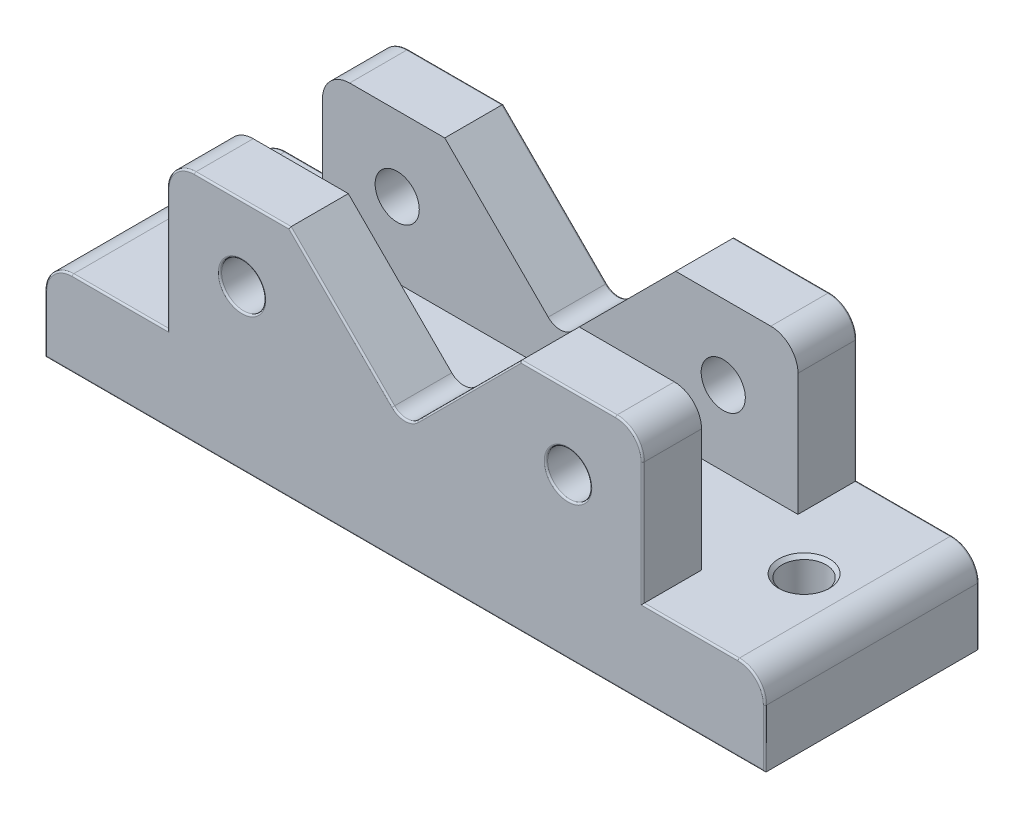
SolidWorks part; units mm, degrees
ref_plane "Płaszczyzna przednia" through (0, 0, 0) normal (0, 0, 1) x (1, 0, 0)
ref_plane "Płaszczyzna górna" through (0, 0, 0) normal (0, 1, 0) x (1, 0, 0)
ref_plane "Płaszczyzna prawa" through (0, 0, 0) normal (1, 0, 0) x (0, 0, -1)
sketch "Sketch1" plane through (0, 0, 0) normal (0, 0, 1) x (1, 0, 0)
  line L0 (0, 50) -> (0, 0) construction
  line L1 (0, 0) -> (106, 0) construction
  line L2 (0, 0) -> (0, 17)
  line L3 (8, 25) -> (36, 25)
  line L4 (36, 25) -> (36, 61)
  line L5 (44, 69) -> (72, 69)
  line L6 (72, 69) -> (102.4645, 38.5355)
  line L7 (106, 0) -> (106, 79.6696) construction
  line L8 (212, 0) -> (212, 17)
  line L9 (140, 69) -> (109.5355, 38.5355)
  line L10 (168, 69) -> (140, 69)
  line L11 (176, 25) -> (176, 61)
  line L12 (204, 25) -> (176, 25)
  line L13 (0, 0) -> (212, 0)
  arc A0 (36, 61) -> (44, 69) centre (44, 61) cw
  arc A1 (0, 17) -> (8, 25) centre (8, 17) cw
  arc A2 (212, 17) -> (204, 25) centre (204, 17) ccw
  arc A3 (176, 61) -> (168, 69) centre (168, 61) ccw
  arc A4 (102.4645, 38.5355) -> (109.5355, 38.5355) centre (106, 42.0711) ccw
  point P12 (36, 69)
  point P15 (0, 25)
  point P25 (212, 25)
  point P26 (176, 69)
  point P27 (0, 0)
  point P30 (106, 35)
  dimension "D7" = 8
  dimension "D8" = 5
  dimension "D1" = 25
  dimension "D2" = 36
  dimension "D3" = 44
  dimension "D4" = 36
  dimension "D5" = 45
  dimension "D6" = 34
extrude "Boss-Extrude1" add sketch "Sketch1" along normal mid plane 63
sketch "Sketch2" plane through (176, 0, 0) normal (1, 0, 0) x (0, 0, -1)
  line L0 (-31.5, 25) -> (31.5, 25) construction
  line L1 (-14.2, 25) -> (14.2, 25)
  line L2 (-14.2, 25) -> (-14.2, 69)
  line L3 (-14.2, 69) -> (14.2, 69)
  line L4 (14.2, 25) -> (14.2, 69)
  line L5 (-14.2, 25) -> (14.2, 69) construction
  line L6 (-14.2, 69) -> (14.2, 25) construction
  line L7 (-31.5, 69) -> (31.5, 69) construction
  line L8 (0, 47) -> (0, 0) construction
  point P4 (0, 47)
  dimension "D1" = 28.4
extrude "Cut-Extrude1" cut sketch "Sketch2" against normal up to next
sketch "Sketch3" plane through (0, 0, 31.5) normal (0, 0, 1) x (1, 0, 0)
  line L0 (58, 47) -> (106, 0) construction
  line L1 (0, 0) -> (212, 0) construction
  line L2 (106, 0) -> (106, 88.6011) construction
  line L3 (72, 69) -> (44, 69) construction
  circle A0 centre (58, 47) radius 6.5
  circle A1 centre (154, 47) radius 6.5
  point P8 (48.3516, 59.3091)
  dimension "D1" = 13
  dimension "D2" = 48
  dimension "D3" = 22
extrude "Cut-Extrude2" cut sketch "Sketch3" against normal through all
sketch "Sketch4" plane through (0, 25, 0) normal (0, 1, 0) x (1, 0, 0)
  line L0 (0, 0) -> (212, 0) construction
  line L1 (212, -31.5) -> (212, 31.5) construction
  line L2 (0, -31.5) -> (0, 31.5) construction
  circle A0 centre (20, 0) radius 6.5
  circle A1 centre (192, 0) radius 6.5
  dimension "D1" = 20
  dimension "D2" = 13
  dimension "D3" = 20
extrude "Cut-Extrude3" cut sketch "Sketch4" against normal through all
fillet "Fillet1" radius 0.5 36 edges at (212, 8.5, -31.5) (209.6569, 22.6569, -31.5) (190, 25, -31.5) (176, 43, -31.5) (173.6569, 66.6569, -31.5) (154, 69, -31.5) (124.7678, 53.7678, -31.5) (106, 37.0711, -31.5) (87.2322, 53.7678, -31.5) (58, 69, -31.5) (38.3431, 66.6569, -31.5) (36, 43, -31.5) (22, 25, -31.5) (2.3431, 22.6569, -31.5) (0, 8.5, -31.5) (106, 0, -31.5) (147.5, 47, -31.5) (64.5, 47, -31.5) (0, 8.5, 31.5) (2.3431, 22.6569, 31.5) (22, 25, 31.5) (36, 43, 31.5) (38.3431, 66.6569, 31.5) (58, 69, 31.5) (87.2322, 53.7678, 31.5) (106, 37.0711, 31.5) (124.7678, 53.7678, 31.5) (154, 69, 31.5) (173.6569, 66.6569, 31.5) (176, 43, 31.5) (190, 25, 31.5) (209.6569, 22.6569, 31.5) (212, 8.5, 31.5) (106, 0, 31.5) (147.5, 47, 31.5) (64.5, 47, 31.5)
chamfer "Chamfer1" distance 1 angle 45 2 edges at (192, 25, 6.5) (20, 25, 6.5)
